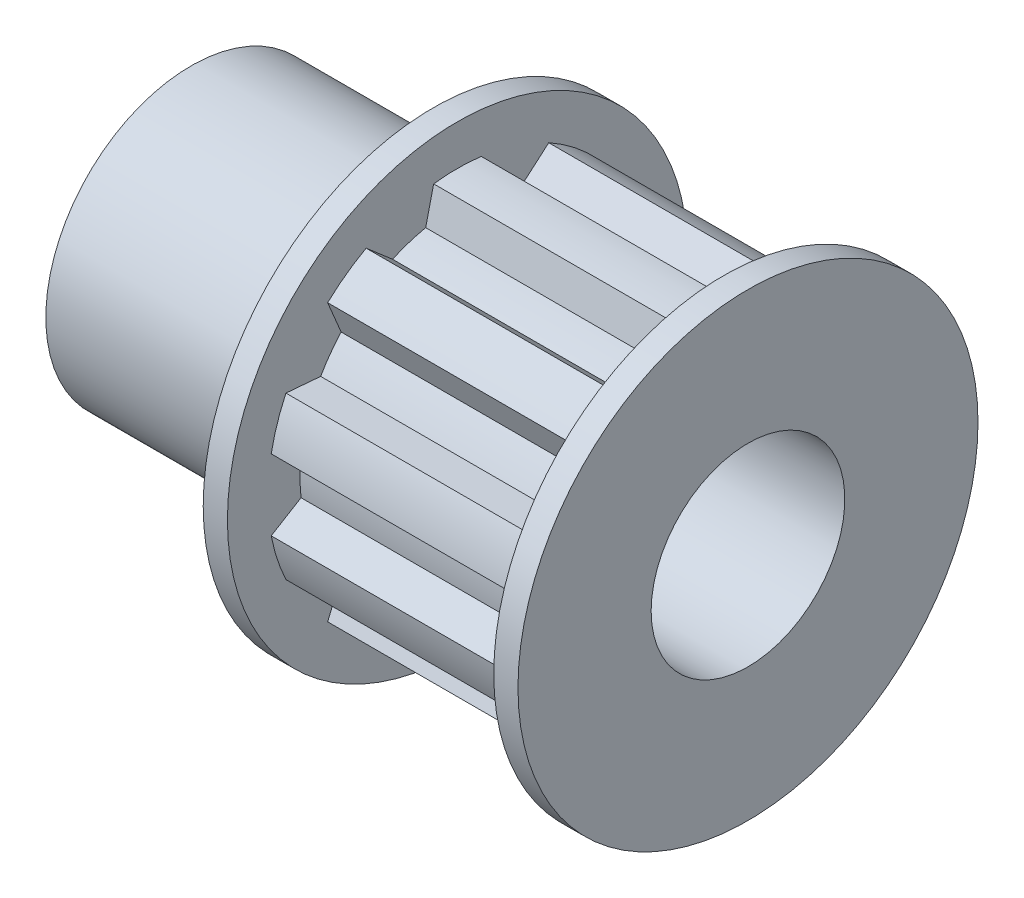
SolidWorks part; units mm, degrees
material "AISI 304"
ref_plane "前视基准面" through (0, 0, 0) normal (0, 0, 1) x (1, 0, 0)
ref_plane "上视基准面" through (0, 0, 0) normal (0, 1, 0) x (1, 0, 0)
ref_plane "右视基准面" through (0, 0, 0) normal (1, 0, 0) x (0, 0, -1)
sketch "Sketch1" plane through (0, 0, 0) normal (1, 0, 0) x (0, 0, -1)
  circle A0 centre (0, 0) radius 6
  dimension "D1" = 12
extrude "Boss-Extrude1" add sketch "Sketch1" along normal blind 10
sketch "Sketch2" plane through (10, 0, 0) normal (1, 0, 0) x (0, 0, -1)
  circle A0 centre (0, 0) radius 9.5
  dimension "D1" = 19
extrude "Boss-Extrude2" add sketch "Sketch2" along normal blind 1
sketch "Sketch3" plane through (11, 0, 0) normal (1, 0, 0) x (0, 0, -1)
  line L0 (0, 10.7415) -> (0, -11.8442) construction
  line L1 (-15.3373, 0) -> (14.9401, 0) construction
  line L2 (-0.9825, 7.7681) -> (-1.3117, 6.3663)
  line L3 (0.9825, 7.7681) -> (1.3117, 6.3663)
  line L4 (3.7712, 6.862) -> (2.6808, 5.9214)
  line L5 (5.3608, 5.7071) -> (4.8032, 4.3794)
  line L6 (7.0843, 3.3349) -> (5.6493, 3.2148)
  line L7 (7.6915, 1.4661) -> (6.46, 0.7198)
  line L8 (7.6915, -1.4661) -> (6.46, -0.7198)
  line L9 (7.0843, -3.3349) -> (5.6493, -3.2148)
  line L10 (5.3608, -5.7071) -> (4.8032, -4.3794)
  line L11 (3.7712, -6.862) -> (2.6808, -5.9214)
  line L12 (0.9825, -7.7681) -> (1.3117, -6.3663)
  line L13 (-0.9825, -7.7681) -> (-1.3117, -6.3663)
  line L14 (-3.7712, -6.862) -> (-2.6808, -5.9214)
  line L15 (-5.3608, -5.7071) -> (-4.8032, -4.3794)
  line L16 (-7.0843, -3.3349) -> (-5.6493, -3.2148)
  line L17 (-7.6915, -1.4661) -> (-6.46, -0.7198)
  line L18 (-7.6915, 1.4661) -> (-6.46, 0.7198)
  line L19 (-7.0843, 3.3349) -> (-5.6493, 3.2148)
  line L20 (-5.3608, 5.7071) -> (-4.8032, 4.3794)
  line L21 (-3.7712, 6.862) -> (-2.6808, 5.9214)
  arc A0 (-3.7712, 6.862) -> (-5.3608, 5.7071) centre (0, 0) ccw
  arc A1 (-1.3117, 6.3663) -> (-2.6808, 5.9214) centre (0, 0) ccw
  arc A2 (0.9825, 7.7681) -> (-0.9825, 7.7681) centre (0, 0) ccw
  arc A3 (2.6808, 5.9214) -> (1.3117, 6.3663) centre (0, 0) ccw
  arc A4 (5.3608, 5.7071) -> (3.7712, 6.862) centre (0, 0) ccw
  arc A5 (7.6915, 1.4661) -> (7.0843, 3.3349) centre (0, 0) ccw
  arc A6 (5.6493, 3.2148) -> (4.8032, 4.3794) centre (0, 0) ccw
  arc A7 (6.46, -0.7198) -> (6.46, 0.7198) centre (0, 0) ccw
  arc A8 (4.8032, -4.3794) -> (5.6493, -3.2148) centre (0, 0) ccw
  arc A9 (1.3117, -6.3663) -> (2.6808, -5.9214) centre (0, 0) ccw
  arc A10 (-2.6808, -5.9214) -> (-1.3117, -6.3663) centre (0, 0) ccw
  arc A11 (-5.6493, -3.2148) -> (-4.8032, -4.3794) centre (0, 0) ccw
  arc A12 (-6.46, 0.7198) -> (-6.46, -0.7198) centre (0, 0) ccw
  arc A13 (-4.8032, 4.3794) -> (-5.6493, 3.2148) centre (0, 0) ccw
  arc A14 (-7.0843, 3.3349) -> (-7.6915, 1.4661) centre (0, 0) ccw
  arc A15 (-7.6915, -1.4661) -> (-7.0843, -3.3349) centre (0, 0) ccw
  arc A16 (-5.3608, -5.7071) -> (-3.7712, -6.862) centre (0, 0) ccw
  arc A17 (-0.9825, -7.7681) -> (0.9825, -7.7681) centre (0, 0) ccw
  arc A18 (3.7712, -6.862) -> (5.3608, -5.7071) centre (0, 0) ccw
  arc A19 (7.0843, -3.3349) -> (7.6915, -1.4661) centre (0, 0) ccw
  point P51 (0, 0)
  dimension "D1" = 15.66
  dimension "D2" = 13
  dimension "D4" = 1.44
  dimension "D5" = 0.9825
  dimension "D3" = 10
extrude "Boss-Extrude3" add sketch "Sketch3" along normal blind 11
sketch "Sketch4" plane through (22, 0, 0) normal (1, 0, 0) x (0, 0, -1)
  circle A0 centre (0, 0) radius 9.5
  dimension "D1" = 19
extrude "Boss-Extrude4" add sketch "Sketch4" along normal blind 1
sketch "Sketch5" plane through (0, 0, 0) normal (-1, 0, 0) x (0, 0, 1)
  circle A0 centre (0, 0) radius 4
  dimension "D1" = 8
extrude "Cut-Extrude1" cut sketch "Sketch5" against normal through all
sketch "Sketch6" plane through (0, 0, 0) normal (0, 1, 0) x (1, 0, 0)
  line L0 (-2.0703, 0) -> (24.008, 0) construction
  line L1 (5, -7.1707) -> (5, 8.3529) construction
  line L2 (0, 6) -> (0, -6) construction
  circle A0 centre (5, 0) radius 2
  dimension "D2" = 4
  dimension "D1" = 5
extrude "Cut-Extrude2" cut sketch "Sketch6" against normal through all
